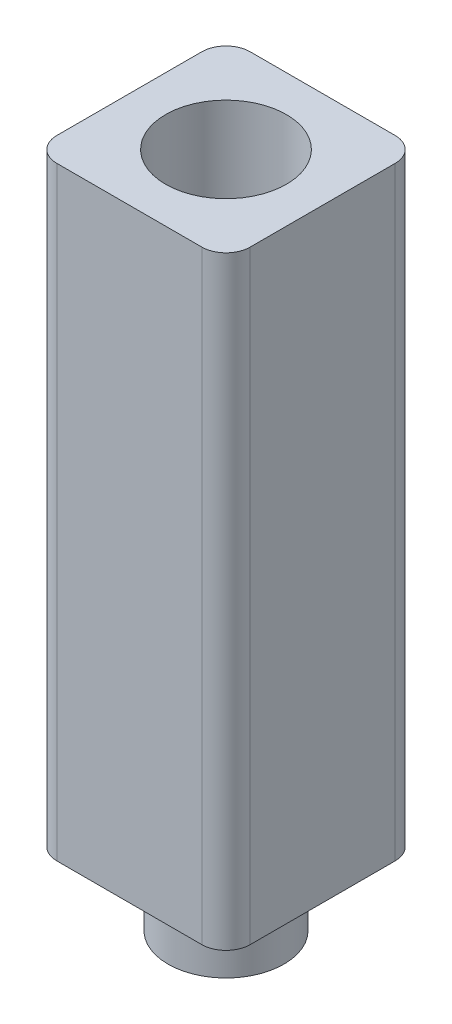
SolidWorks part; units mm, degrees
ref_plane "Plan de face" through (0, 0, 0) normal (0, 0, 1) x (1, 0, 0)
ref_plane "Plan de dessus" through (0, 0, 0) normal (0, 1, 0) x (1, 0, 0)
ref_plane "Plan de droite" through (0, 0, 0) normal (1, 0, 0) x (0, 0, -1)
sketch "Sketch1" plane through (0, 0, 0) normal (0, 1, 0) x (1, 0, 0)
  circle A0 centre (0, 0) radius 2.4
  dimension "D1" = 4.8
extrude "Boss-Extrude1" add sketch "Sketch1" along normal blind 3
sketch "Sketch2" plane through (0, 3, 0) normal (0, 1, 0) x (1, 0, 0)
  line L1 (-4, -4) -> (4, -4)
  line L2 (-4, -4) -> (-4, 4)
  line L3 (-4, 4) -> (4, 4)
  line L4 (4, -4) -> (4, 4)
  line L5 (-4, -4) -> (4, 4) construction
  line L6 (-4, 4) -> (4, -4) construction
  point P0 (0, 0)
  dimension "D1" = 8
  dimension "D2" = 8
extrude "Boss-Extrude2" add sketch "Sketch2" along normal blind 25
sketch "Sketch3" plane through (0, 28, 0) normal (0, 1, 0) x (1, 0, 0)
  circle A2 centre (0, 0) radius 2.5
  dimension "D1" = 5
extrude "Cut-Extrude1" cut sketch "Sketch3" against normal blind 4
fillet "Fillet1" radius 1 4 edges at (-4, 15.5, -4) (-4, 15.5, 4) (4, 15.5, -4) (4, 15.5, 4)
equation "\"D2@Sketch2\"=\"D1@Sketch2\""
